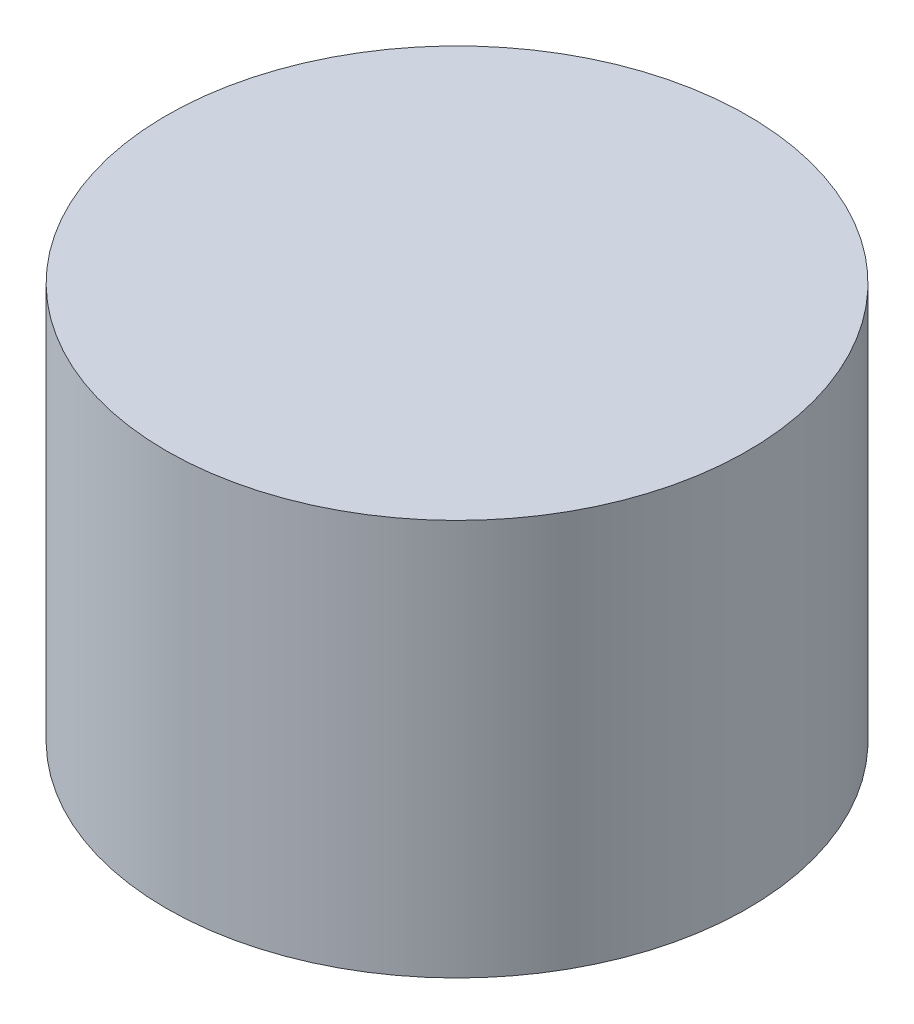
SolidWorks part; units mm, degrees
ref_plane "Front Plane" through (0, 0, 0) normal (0, 0, 1) x (1, 0, 0)
ref_plane "Top Plane" through (0, 0, 0) normal (0, 1, 0) x (1, 0, 0)
ref_plane "Right Plane" through (0, 0, 0) normal (1, 0, 0) x (0, 0, -1)
sketch "SK_P01_Speaker44mm" plane through (0, 0, 0) normal (0, 1, 0) x (1, 0, 0)
  circle A0 centre (0, 0) radius 22
extrude "P01_Speaker44mm" add sketch "SK_P01_Speaker44mm" along normal blind 30
